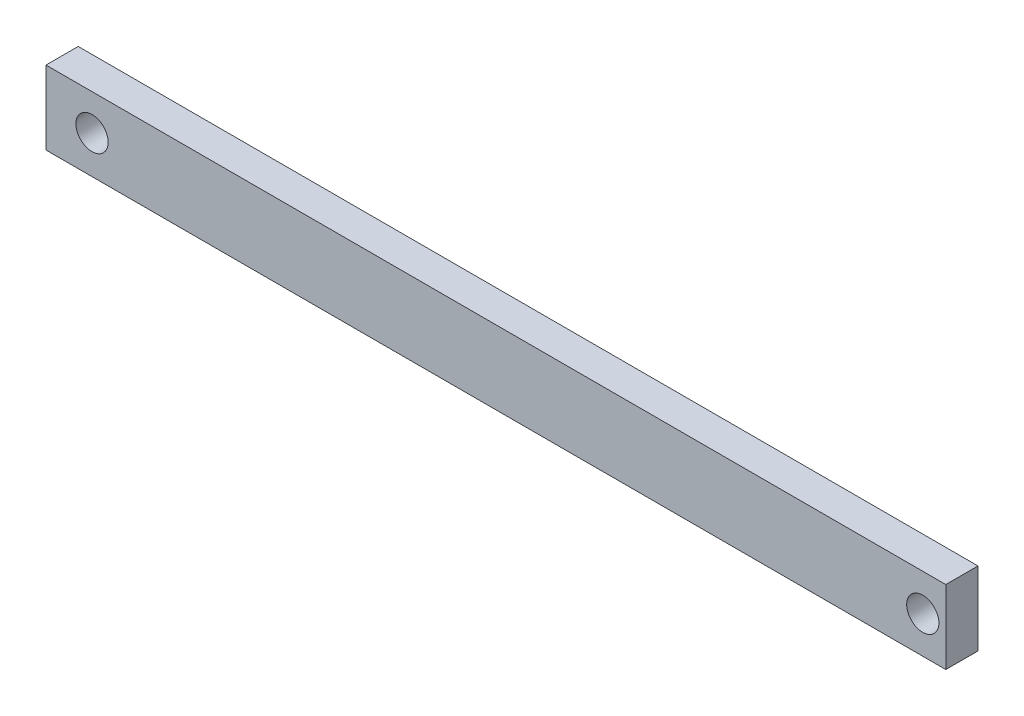
SolidWorks part; units mm, degrees
material "AA356.0-F"
ref_plane "Front Plane" through (0, 0, 0) normal (0, 0, 1) x (1, 0, 0)
ref_plane "Top Plane" through (0, 0, 0) normal (0, 1, 0) x (1, 0, 0)
ref_plane "Right Plane" through (0, 0, 0) normal (1, 0, 0) x (0, 0, -1)
sketch "Sketch1" plane through (0, 0, 0) normal (0, 0, 1) x (1, 0, 0)
  line L1 (-237.8571, 26.2857) -> (153.1429, 26.2857)
  line L2 (-237.8571, 26.2857) -> (-237.8571, -5.7143)
  line L3 (-237.8571, -5.7143) -> (153.1429, -5.7143)
  line L4 (153.1429, 26.2857) -> (153.1429, -5.7143)
  dimension "D1" = 32
  dimension "D2" = 391
extrude "Boss-Extrude1" add sketch "Sketch1" along normal blind 14
sketch "Sketch2" plane through (0, 0, 14) normal (0, 0, 1) x (1, 0, 0)
  line L0 (-237.8571, 26.2857) -> (-237.8571, -5.7143) construction
  circle A0 centre (-217.8571, 10.6917) radius 7
  point P4 (-237.8571, 10.2857)
  dimension "D1" = 20
extrude "Cut-Extrude1" cut sketch "Sketch2" against normal through all
sketch "Sketch3" plane through (0, 0, 14) normal (0, 0, 1) x (1, 0, 0)
  line L1 (153.1429, -5.7143) -> (153.1429, 26.2857) construction
  circle A2 centre (143.1429, 10.2857) radius 7
  point P4 (153.1429, 10.2857)
  dimension "D1" = 10
extrude "Cut-Extrude2" cut sketch "Sketch3" against normal through all
